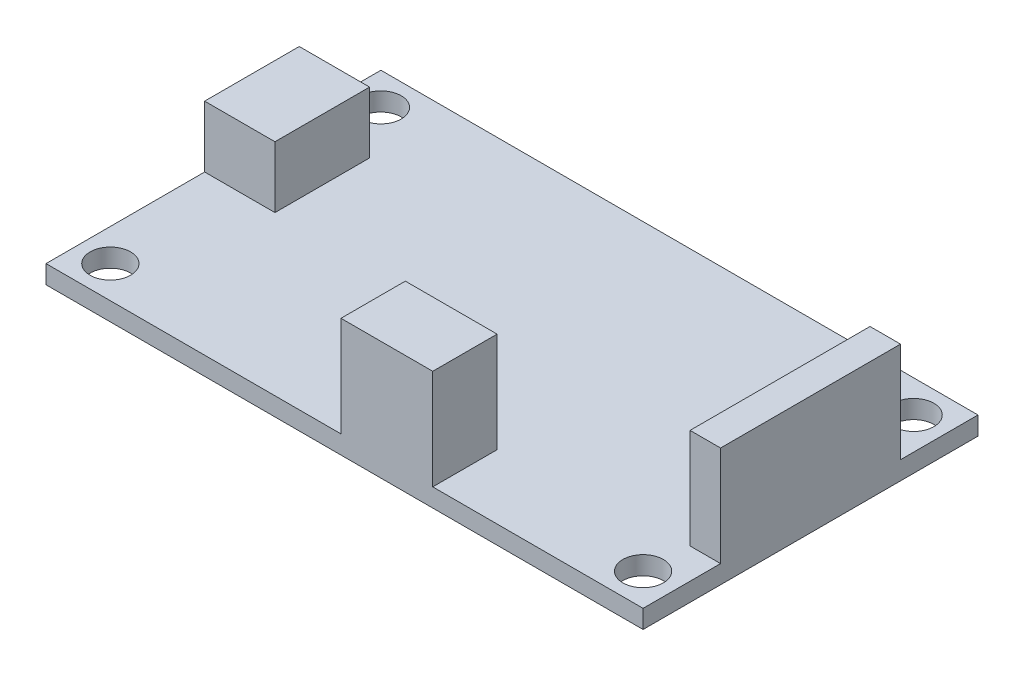
SolidWorks part; units mm, degrees
ref_plane "Front Plane" through (0, 0, 0) normal (0, 0, 1) x (1, 0, 0)
ref_plane "Top Plane" through (0, 0, 0) normal (0, 1, 0) x (1, 0, 0)
ref_plane "Right Plane" through (0, 0, 0) normal (1, 0, 0) x (0, 0, -1)
sketch "Sketch1" plane through (0, 0, 0) normal (0, 1, 0) x (1, 0, 0)
  line L0 (-96.4227, 28.9216) -> (-96.4227, 29.9216) construction
  line L1 (-99.1227, 29.9216) -> (-49.0227, 29.9216)
  line L2 (-99.1227, 29.9216) -> (-99.1227, 1.8216)
  line L4 (-49.0227, 29.9216) -> (-49.0227, 1.8216)
  line L5 (-98.1227, 27.2216) -> (-99.1227, 27.2216) construction
  line L6 (-74.0727, 29.9216) -> (-74.0727, 1.8216) construction
  line L7 (-50.0227, 27.2216) -> (-49.0227, 27.2216) construction
  line L8 (-51.7227, 28.9216) -> (-51.7227, 29.9216) construction
  line L9 (-99.1227, 15.8716) -> (-49.0227, 15.8716) construction
  line L10 (-51.7227, 2.8216) -> (-51.7227, 1.8216) construction
  line L11 (-50.0227, 4.5216) -> (-49.0227, 4.5216) construction
  line L12 (-98.1227, 4.5216) -> (-99.1227, 4.5216) construction
  line L13 (-96.4227, 2.8216) -> (-96.4227, 1.8216) construction
  line L14 (-99.1227, 1.8216) -> (-49.0227, 1.8216)
  circle A0 centre (-96.4227, 27.2216) radius 1.7
  circle A1 centre (-51.7227, 27.2216) radius 1.7
  circle A2 centre (-51.7227, 4.5216) radius 1.7
  circle A3 centre (-96.4227, 4.5216) radius 1.7
  dimension "D3" = 3.4
  dimension "D1" = 28.1
  dimension "D2" = 50.1
  dimension "D4" = 1
  dimension "D5" = 1
extrude "Extrude1" add sketch "Sketch1" along normal blind 1.54
sketch "Sketch2" plane through (0, 1.54, 0) normal (0, 1, 0) x (1, 0, 0)
  line L0 (-49.0227, 1.8216) -> (-49.0227, 29.9216) construction
  line L1 (-49.0227, 23.4216) -> (-51.5827, 23.4216)
  line L2 (-49.0227, 23.4216) -> (-49.0227, 8.3216)
  line L3 (-49.0227, 8.3216) -> (-51.5827, 8.3216)
  line L4 (-51.5827, 23.4216) -> (-51.5827, 8.3216)
  line L5 (-51.5827, 23.4216) -> (-51.5827, 29.9216) construction
  line L6 (-49.0227, 29.9216) -> (-99.1227, 29.9216) construction
  line L7 (-51.5827, 8.3216) -> (-51.5827, 1.8216) construction
  line L8 (-99.1227, 1.8216) -> (-49.0227, 1.8216) construction
  line L10 (-66.6727, 1.8216) -> (-74.3727, 1.8216)
  line L11 (-66.6727, 1.8216) -> (-66.6727, 7.2216)
  line L12 (-66.6727, 7.2216) -> (-74.3727, 7.2216)
  line L13 (-74.3727, 1.8216) -> (-74.3727, 7.2216)
  dimension "D1" = 2.56
  dimension "D2" = 15.1
  dimension "D3" = 5.4
  dimension "D4" = 7.7
  dimension "D5" = 17.65
extrude "Extrude3" add sketch "Sketch2" along normal blind 8.4
sketch "Sketch3" plane through (0, 1.54, 0) normal (0, 1, 0) x (1, 0, 0)
  line L0 (-99.1227, 29.9216) -> (-99.1227, 1.8216) construction
  line L1 (-99.1227, 23.0716) -> (-93.2227, 23.0716)
  line L2 (-99.1227, 23.0716) -> (-99.1227, 15.1316)
  line L3 (-99.1227, 15.1316) -> (-93.2227, 15.1316)
  line L4 (-93.2227, 23.0716) -> (-93.2227, 15.1316)
  line L5 (-49.0227, 29.9216) -> (-99.1227, 29.9216) construction
  dimension "D1" = 5.9
  dimension "D2" = 7.94
  dimension "D3" = 6.85
extrude "Extrude4" add sketch "Sketch3" along normal blind 5.15
